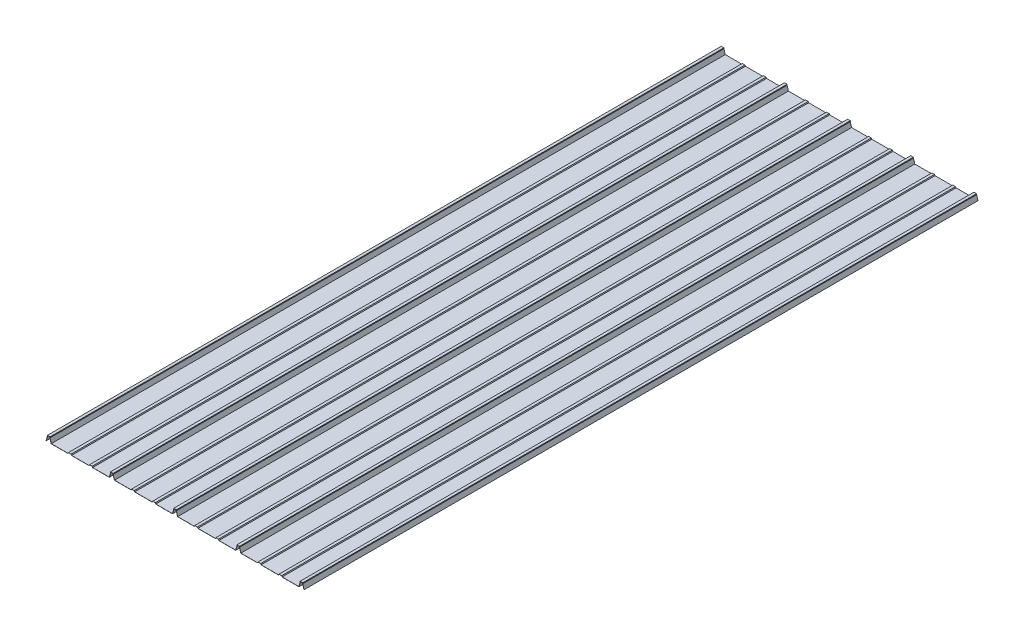
SolidWorks part; units mm, degrees
ref_plane "Front Plane" through (0, 0, 0) normal (0, 0, 1) x (1, 0, 0)
ref_plane "Top Plane" through (0, 0, 0) normal (0, 1, 0) x (1, 0, 0)
ref_plane "Right Plane" through (0, 0, 0) normal (1, 0, 0) x (0, 0, -1)
sketch "Sketch1" plane through (0, 0, 0) normal (0, 0, 1) x (1, 0, 0)
  line L0 (5.2705, 15.875) -> (5.2705, 18.542)
  line L1 (4.7625, 19.05) -> (14.2875, 19.05)
  line L2 (5.2705, 18.542) -> (13.7795, 18.542)
  line L3 (9.525, 19.05) -> (9.525, 15.875)
  line L4 (9.525, 15.875) -> (14.2875, 15.875)
  line L5 (9.525, 15.875) -> (4.7625, 15.875)
  line L6 (0, 0) -> (4.7625, 15.875)
  line L7 (4.7625, 15.875) -> (4.7625, 19.05)
  line L8 (14.2875, 15.875) -> (14.2875, 19.05)
  line L9 (19.05, 0) -> (14.2875, 15.875)
  line L10 (13.7795, 15.875) -> (13.7795, 18.542)
  line L11 (9.525, 0) -> (238.125, 0)
  line L12 (123.825, 0) -> (123.825, 26.9522)
  line L13 (247.1634, -0.146) -> (247.4649, -1.1508)
  line L14 (9.525, 0) -> (85.725, 0)
  line L15 (85.725, 0) -> (85.725, 3.175)
  line L16 (85.725, 3.175) -> (80.9625, 3.175)
  line L17 (85.725, 3.175) -> (90.4875, 3.175)
  line L18 (90.4875, 3.175) -> (90.4875, 0)
  line L19 (80.9625, 3.175) -> (80.9625, 0)
  line L20 (80.9625, 3.175) -> (79.1294, 0)
  line L21 (90.4875, 3.175) -> (92.3206, 0)
  line L22 (247.65, 0) -> (247.9952, -1.1508)
  line L23 (229.0866, -0.146) -> (228.8304, -0.9998)
  line L24 (229.9045, -0.508) -> (252.6897, -0.508)
  line L25 (168.5206, -0.508) -> (229.9045, -0.508)
  line L26 (155.3294, -0.508) -> (157.1625, 2.667)
  line L27 (155.3294, 0) -> (155.3294, -0.508)
  line L28 (157.1625, 2.667) -> (166.6875, 2.667)
  line L29 (168.5206, -0.508) -> (166.6875, 2.667)
  line L30 (0.4866, -0.146) -> (5.2491, 15.729)
  line L31 (18.5634, -0.146) -> (13.8009, 15.729)
  line L32 (80.9625, 3.175) -> (80.9625, 2.667)
  line L33 (79.1294, 0) -> (79.1294, -0.508)
  line L34 (79.1294, -0.508) -> (80.9625, 2.667)
  line L35 (90.4875, 2.667) -> (80.9625, 2.667)
  line L36 (92.3206, 0) -> (92.3206, -0.508)
  line L37 (92.3206, -0.508) -> (90.4875, 2.667)
  line L38 (79.1294, -0.508) -> (17.7455, -0.508)
  line L39 (17.7455, -0.508) -> (-5.0397, -0.508)
  line L40 (18.5634, -0.146) -> (18.8196, -0.9998)
  line L41 (0, 0) -> (-0.3452, -1.1508)
  line L42 (0.4866, -0.146) -> (0.1851, -1.1508)
  line L43 (92.3206, -0.508) -> (155.3294, -0.508)
  line L44 (123.825, -0.508) -> (123.825, 0.062)
  line L45 (168.5206, 0) -> (168.5206, -0.508)
  line L46 (166.6875, 3.175) -> (166.6875, 2.667)
  line L47 (229.0866, -0.146) -> (233.8491, 15.729)
  line L48 (247.1634, -0.146) -> (242.4009, 15.729)
  line L49 (157.1625, 3.175) -> (155.3294, 0)
  line L50 (166.6875, 3.175) -> (168.5206, 0)
  line L51 (166.6875, 3.175) -> (166.6875, 0)
  line L52 (157.1625, 3.175) -> (157.1625, 0)
  line L53 (161.925, 3.175) -> (157.1625, 3.175)
  line L54 (161.925, 3.175) -> (166.6875, 3.175)
  line L55 (161.925, 0) -> (161.925, 3.175)
  line L56 (238.125, 0) -> (161.925, 0)
  line L57 (233.8705, 15.875) -> (233.8705, 18.542)
  line L58 (228.6, 0) -> (233.3625, 15.875)
  line L59 (233.3625, 15.875) -> (233.3625, 19.05)
  line L60 (242.8875, 15.875) -> (242.8875, 19.05)
  line L61 (247.65, 0) -> (242.8875, 15.875)
  line L62 (238.125, 15.875) -> (242.8875, 15.875)
  line L63 (238.125, 15.875) -> (233.3625, 15.875)
  line L64 (238.125, 19.05) -> (238.125, 15.875)
  line L65 (242.3795, 18.542) -> (233.8705, 18.542)
  line L66 (242.8875, 19.05) -> (233.3625, 19.05)
  line L67 (242.3795, 15.875) -> (242.3795, 18.542)
  line L68 (13.7795, 15.875) -> (13.8009, 15.729)
  line L69 (233.8491, 15.729) -> (233.8705, 15.875)
  line L70 (242.4009, 15.729) -> (242.3795, 15.875)
  arc A0 (5.2491, 15.729) -> (5.2705, 15.875) centre (4.7625, 15.875) ccw
  dimension "D1" = 0.508
  dimension "D2" = 0.508
  dimension "D3" = 0.508
extrude "Boss-Extrude1" add sketch "Sketch1" along normal blind 2438.4 contours L7 L5 L0 L2 L3 L1 | L30 A0 L5 L6 L41 L39 L42 | L10 L4 L8 L1 L3 L2 | L4 L68 L31 L14 L9 | L31 L40 L38 L33 L11 L14 | L33 L34 L14 | L14 L34 L19 L20 | L35 L15 L16 L19 | L37 L36 L11 | L37 L11 L21 L18 | L35 L18 L17 L15 | L43 L44 L11 L36 | L44 L43 L27 L11 | L11 L27 L26 | L52 L49 L11 L26 | L28 L55 L53 L52 | L55 L28 L46 L54 | L50 L46 L29 L11 | L45 L11 L29 | L23 L47 L56 L11 L45 L25 | L47 L69 L63 L58 L56 | L64 L66 L59 L63 L57 L65 | L67 L62 L60 L66 L64 L65 | L70 L48 L13 L24 L22 L61 L62
pattern_linear "LPattern1" count 4 spacing 228.6 along (1, 0, 0) of "Boss-Extrude1"
